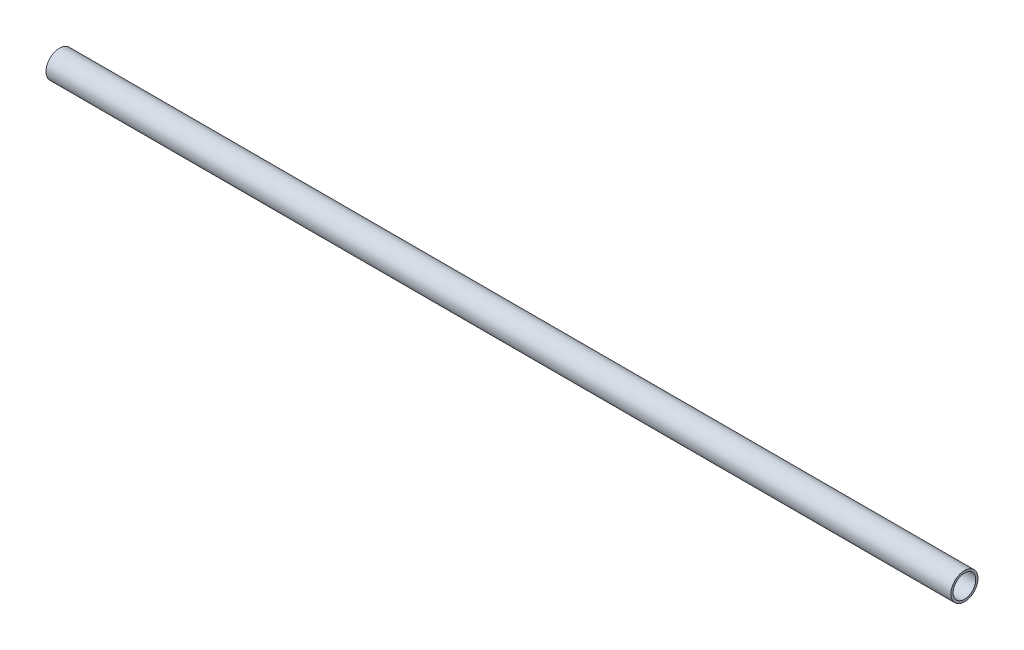
SolidWorks part; units mm, degrees
ref_plane "Front Plane" through (0, 0, 0) normal (0, 0, 1) x (1, 0, 0)
ref_plane "Top Plane" through (0, 0, 0) normal (0, 1, 0) x (1, 0, 0)
ref_plane "Right Plane" through (0, 0, 0) normal (1, 0, 0) x (0, 0, -1)
sketch "Sketch1" plane through (0, 0, 0) normal (0, 0, 1) x (1, 0, 0)
  line L0 (0, -44.7868) -> (0, 44.7868) construction
  line L1 (55, 0) -> (-55, 0) construction
  line L6 (-74.1486, 0) -> (71.716, 0) construction
  line L7 (-100, 5) -> (300, 5)
  line L9 (-100, 5) -> (-100, 6)
  line L10 (-100, 6) -> (300, 6)
  line L11 (300, 5) -> (300, 6)
  dimension "D1" = 6
  dimension "D2" = 400
  dimension "D3" = 100
  dimension "D4" = 5
revolve "Revolve1" add sketch "Sketch1" angle 360 about L6
